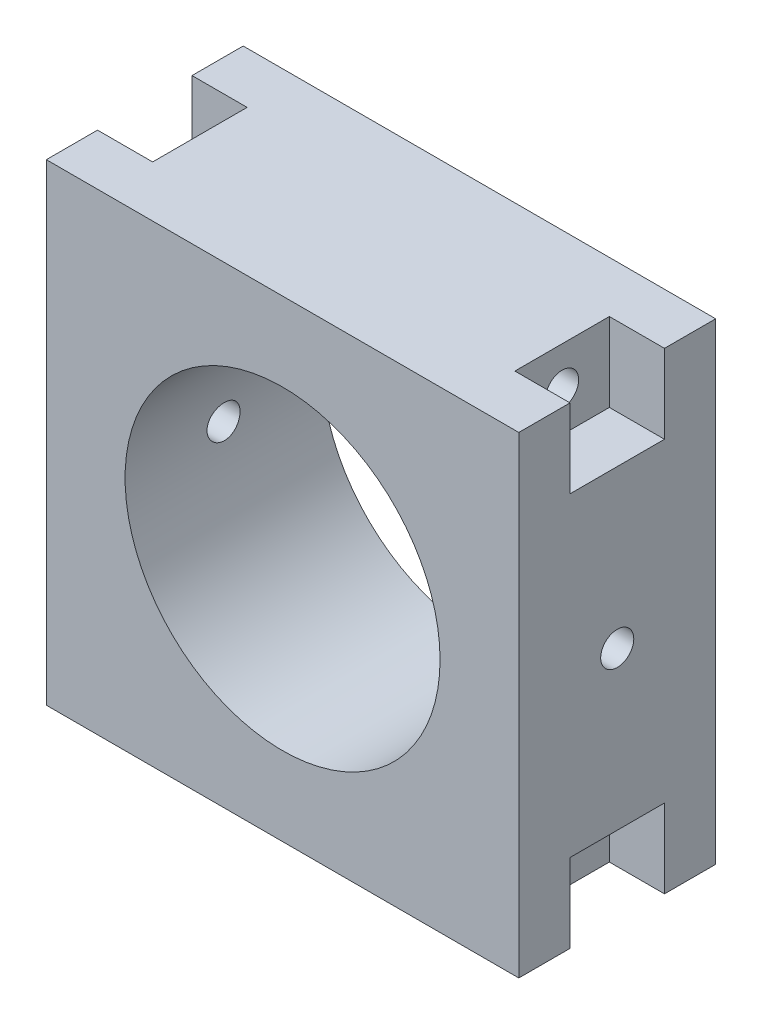
SolidWorks part; units mm, degrees
ref_plane "Front Plane" through (0, 0, 0) normal (0, 0, 1) x (1, 0, 0)
ref_plane "Top Plane" through (0, 0, 0) normal (0, 1, 0) x (1, 0, 0)
ref_plane "Right Plane" through (0, 0, 0) normal (1, 0, 0) x (0, 0, -1)
sketch "Sketch1" plane through (0, 0, 0) normal (0, 0, 1) x (1, 0, 0)
  line L0 (0, 0) -> (0, 191362.0965) construction
  line L1 (0, 0) -> (191362.0965, 0) construction
  line L2 (-20, 0) -> (-30, 0)
  line L3 (-30, -30) -> (-30, 30)
  line L4 (-30, 30) -> (30, 30)
  line L5 (20, 0) -> (30, 0)
  line L6 (30, -30) -> (30, 30)
  line L7 (-30, -30) -> (30, -30)
  circle A0 centre (0, 0) radius 20
  point P13 (0, 30)
  dimension "D1" = 20
  dimension "D2" = 60
  dimension "D3" = 30
extrude "Boss-Extrude1" add sketch "Sketch1" along normal blind 25 contours A0 L5 L6 L4 L3 L2 | A0 L2 L3 L7 L6 L5
sketch "Sketch2" plane through (30, 0, 0) normal (1, 0, 0) x (0, 0, -1)
  line L0 (-12.5, 30) -> (-12.5, -30) construction
  line L1 (-25, 30) -> (0, 30) construction
  line L3 (-25, 30) -> (0, 30) construction
  line L4 (-25, -30) -> (0, -30) construction
  line L5 (0, 0) -> (-25, 0) construction
  line L6 (-25, -30) -> (-25, 30) construction
  circle A0 centre (-12.5, 25) radius 2.1
  circle A1 centre (-12.5, -25) radius 2.1
  circle A2 centre (-12.5, 0) radius 2.1
  dimension "D1" = 4.2
  dimension "D2" = 5
  dimension "D3" = 5
extrude "Cut-Extrude1" cut sketch "Sketch2" against normal through all
fillet "Fillet1" [suppressed] radius 20
sketch "Sketch3" plane through (0, 30, 0) normal (0, 1, 0) x (1, 0, 0)
  line L0 (-30, -12.5) -> (30, -12.5) construction
  line L1 (-30, -25) -> (-30, 0) construction
  line L2 (30, -25) -> (30, 0) construction
  line L3 (-23, -18.5) -> (-23, -6.5)
  line L4 (-23, -18.5) -> (-30, -18.5)
  line L5 (-23, -6.5) -> (-30, -6.5)
  line L6 (-30, -18.5) -> (-30, -6.5)
  line L7 (-23, -18.5) -> (-30, -6.5) construction
  line L8 (-23, -6.5) -> (-30, -18.5) construction
  line L9 (0, 0) -> (0, -25) construction
  line L10 (-30, 0) -> (30, 0) construction
  line L11 (-30, -25) -> (30, -25) construction
  line L12 (30, -18.5) -> (30, -6.5)
  line L13 (23, -18.5) -> (30, -18.5)
  line L14 (23, -18.5) -> (23, -6.5)
  line L15 (23, -6.5) -> (30, -6.5)
  line L17 (-23, -15) -> (23, -15)
  line L18 (-23, -15) -> (-23, -10)
  line L19 (-23, -10) -> (23, -10)
  line L20 (23, -15) -> (23, -10)
  line L21 (-23, -15) -> (23, -10) construction
  line L22 (-23, -10) -> (23, -15) construction
  point P7 (-26.5, -12.5)
  point P21 (0, -12.5)
  line M10 (-30, 0) -> (-30, -25)
  line M12 (30, -25) -> (30, 0)
  dimension "D1" = 7
  dimension "D2" = 12
  dimension "D3" = 5
extrude "Cut-Extrude2" cut sketch "Sketch3" against normal blind 10 contours L3 L5 L4 M10 | L15 L14 L13 M12
mirror "Mirror1" about plane through (0, 0, 0) normal (0, 1, 0) of "Cut-Extrude2"
